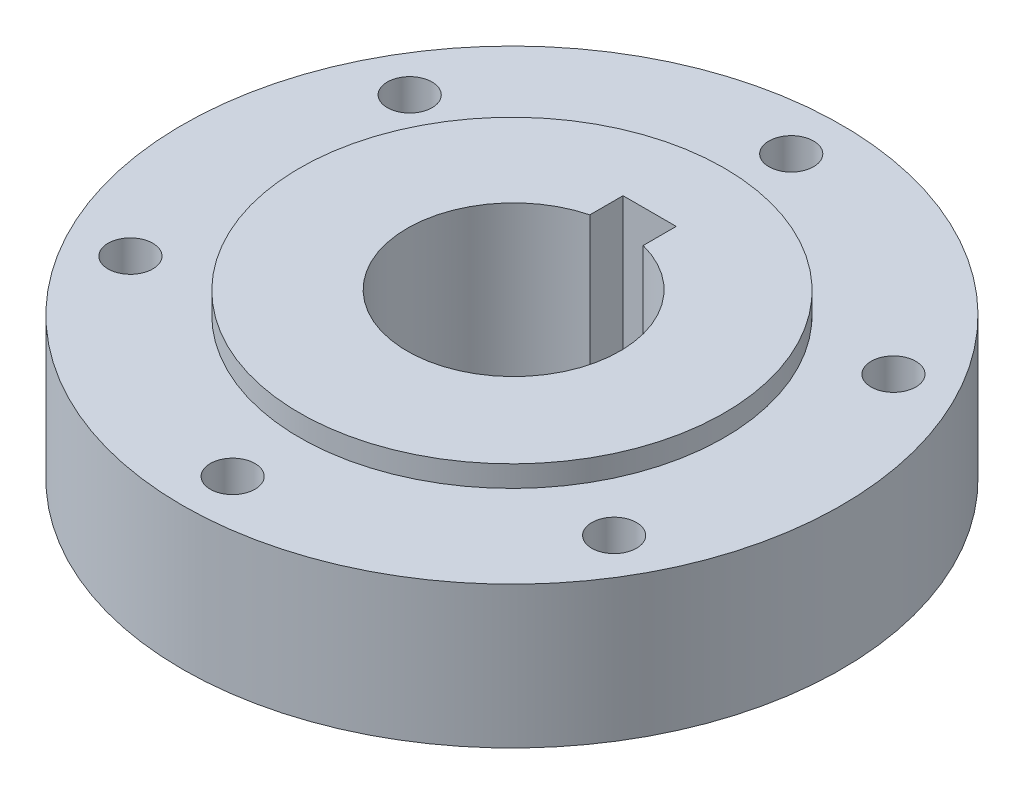
SolidWorks part; units mm, degrees
ref_plane "Front Plane" through (0, 0, 0) normal (0, 0, 1) x (1, 0, 0)
ref_plane "Top Plane" through (0, 0, 0) normal (0, 1, 0) x (1, 0, 0)
ref_plane "Right Plane" through (0, 0, 0) normal (1, 0, 0) x (0, 0, -1)
sketch "Sketch1" plane through (0, 0, 0) normal (0, 1, 0) x (1, 0, 0)
  circle A0 centre (0, 0) radius 29.5
  dimension "D1" = 59
extrude "Boss-Extrude1" add sketch "Sketch1" along normal blind 12.7
sketch "Sketch2" plane through (0, 12.7, 0) normal (0, 1, 0) x (1, 0, 0)
  circle A0 centre (0, 0) radius 19
  dimension "D1" = 38
extrude "Boss-Extrude2" add sketch "Sketch2" along normal blind 1.905
hole_wizard "3/4 (0.75) Diameter Hole1" positions "3DSketch1" profile "Sketch5" hole size "3/4" standard "ANSI Inch"
sketch3d "3DSketch1"
  point P0 (0, 0, 0)
  point P3 (0, 0, 0)
  point P5 (0, 0, 0)
  point P7 (0.0103, 14.605, -0.1385)
sketch "Sketch5" plane through (0.0103, 14.605, -0.1385) normal (1, 0, 0) x (0, 0, 1)
  line L0 (0, 0) -> (0, 14.605)
  line L1 (0, 14.605) -> (9.525, 14.605)
  line L2 (9.525, 14.605) -> (9.525, 0)
  line L5 (9.525, 0) -> (0, 0)
  line L11 (0, -6.35) -> (0, 107.95) construction
  dimension "Thru Hole Dia." = 19.05
  dimension "Thru Hole Depth" = 14.605
sketch "Sketch7" plane through (0, 12.7, 0) normal (0, 1, 0) x (1, 0, 0)
  circle A0 centre (0, 25) radius 2
  circle A1 centre (21.6506, 12.5) radius 2
  circle A2 centre (21.6506, -12.5) radius 2
  circle A3 centre (0, -25) radius 2
  circle A4 centre (-21.6506, -12.5) radius 2
  circle A5 centre (-21.6506, 12.5) radius 2
  point P15 (0, 0)
  dimension "D1" = 6
extrude "Cut-Extrude1" cut sketch "Sketch7" against normal through all both and the other way through all
sketch "Sketch8" plane through (0, 14.605, 0) normal (0, 1, 0) x (1, 0, 0)
  line L0 (0, 0) -> (0, 7.5632) construction
  line L1 (-2.3813, 12.3257) -> (2.3813, 12.3257)
  line L2 (-2.3813, 12.3257) -> (-2.3813, 7.5632)
  line L3 (-2.3813, 7.5632) -> (2.3813, 7.5632)
  line L4 (2.3813, 12.3257) -> (2.3813, 7.5632)
extrude "Cut-Extrude2" cut sketch "Sketch8" against normal through all
